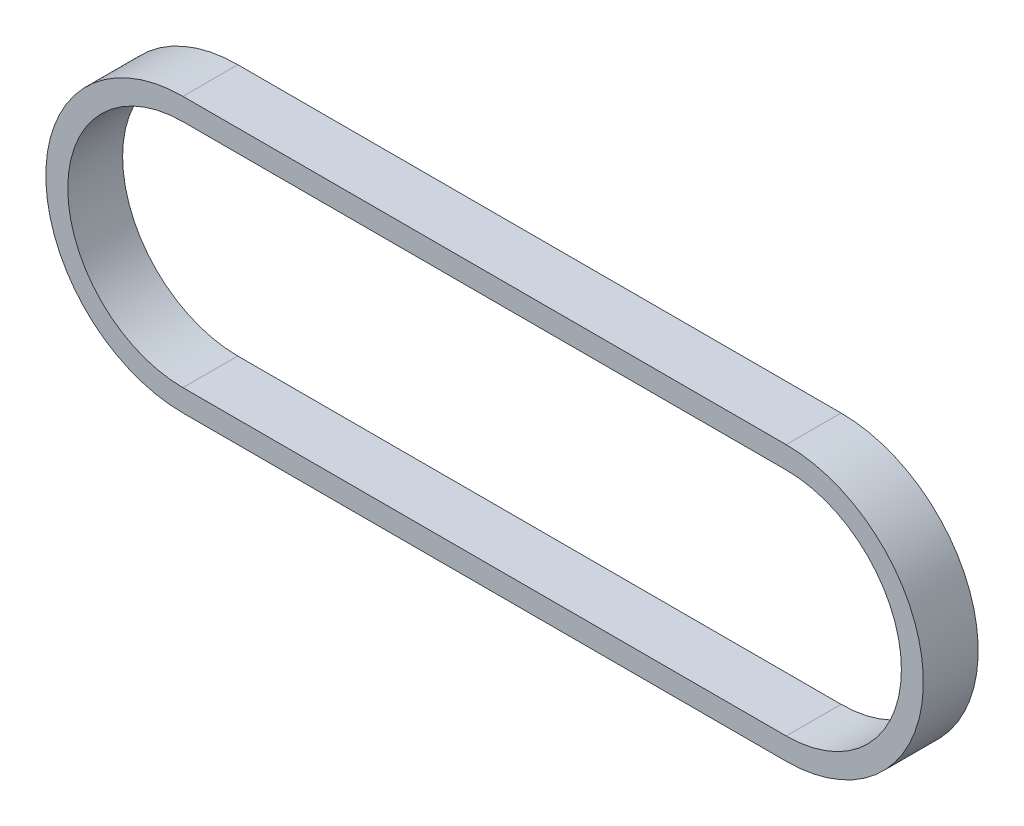
SolidWorks part; units mm, degrees
ref_plane "Front Plane" through (0, 0, 0) normal (0, 0, 1) x (1, 0, 0)
ref_plane "Top Plane" through (0, 0, 0) normal (0, 1, 0) x (1, 0, 0)
ref_plane "Right Plane" through (0, 0, 0) normal (1, 0, 0) x (0, 0, -1)
sketch "Sketch2" plane through (0, 0, 0) normal (0, 0, 1) x (1, 0, 0)
  line L0 (0, 0) -> (1, 0) construction
  line L1 (0, 0) -> (0, 1) construction
  line L2 (0, -21) -> (-110, -21)
  line L3 (-110, 21) -> (0, 21)
  arc A0 (0, 21) -> (0, -21) centre (0, 0) cw
  arc A1 (-110, -21) -> (-110, 21) centre (-110, 0) cw
sketch "Sketch3" plane through (0, 0, 0) normal (0, 0, 1) x (1, 0, 0)
  line L0 (0, -21) -> (-110, -21) construction
  line L1 (-110, 21) -> (0, 21) construction
  line L2 (0, -21) -> (-110, -21)
  line L3 (-110, 21) -> (0, 21)
  line L4 (0, -25) -> (-110, -25)
  line L5 (-110, 25) -> (0, 25)
  arc A0 (0, -21) -> (0, 21) centre (0, 0) ccw construction
  arc A1 (-110, 21) -> (-110, -21) centre (-110, 0) ccw construction
  arc A2 (0, -21) -> (0, 21) centre (0, 0) ccw
  arc A3 (-110, 21) -> (-110, -21) centre (-110, 0) ccw
  arc A4 (-110, 25) -> (-110, -25) centre (-110, 0) ccw
  arc A5 (0, -25) -> (0, 25) centre (0, 0) ccw
  dimension "D1" = 4
extrude "Boss-Extrude1" add sketch "Sketch3" along normal blind 10
